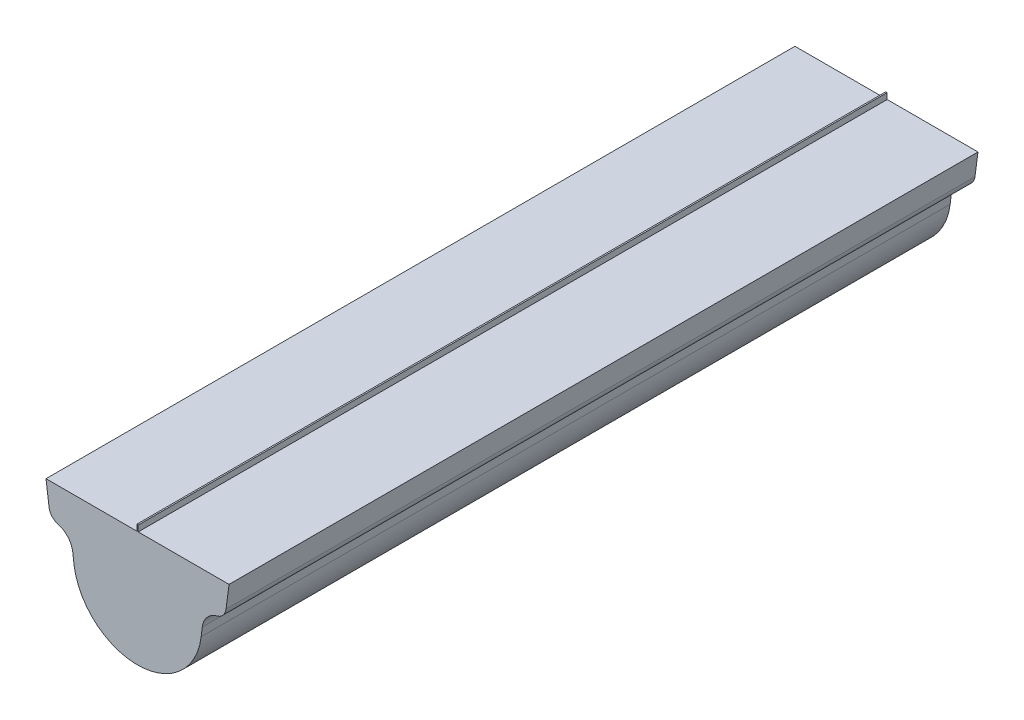
SolidWorks part; units mm, degrees
ref_plane "Front Plane" through (0, 0, 0) normal (0, 0, 1) x (1, 0, 0)
ref_plane "Top Plane" through (0, 0, 0) normal (0, 1, 0) x (1, 0, 0)
ref_plane "Right Plane" through (0, 0, 0) normal (1, 0, 0) x (0, 0, -1)
sketch "Sketch2" plane through (0, 0, 0) normal (0, 0, 1) x (1, 0, 0)
  line L0 (-2.5934, 0.0458) -> (-2.5383, -0.4019)
  line L1 (2.551, -0.3125) -> (2.5948, 0.0454)
  line L2 (3.4932, 0.7413) -> (3.6667, 2.0599)
  line L3 (-3.4918, 0.7413) -> (-3.6652, 2.0599)
  line L4 (-3.6652, 2.0599) -> (-0.0275, 2.0599)
  line L5 (0.0007, 2.3) -> (0.0007, 2.0599) construction
  line L6 (0.0289, 2.0599) -> (3.6667, 2.0599)
  line L10 (0.0289, 2.2587) -> (0.0289, 2.0599)
  line L11 (-0.0238, 2.3) -> (0.0289, 2.042) construction
  line L12 (-0.0275, 2.042) -> (0.0253, 2.3) construction
  line L13 (-0.0275, 2.2587) -> (-0.0275, 2.0599)
  line L14 (0.0289, 2.2587) -> (0.0289, 2.3)
  line L15 (0.0289, 2.3) -> (-0.0275, 2.3)
  line L20 (-0.0275, 2.3) -> (-0.0275, 2.2587)
  line L21 (0.0001, 0) -> (0.0007, 2.0599) construction
  arc A0 (-2.5934, 0.0458) -> (-3.4918, 0.7413) centre (-3.3874, -0.0519) ccw
  arc A1 (3.4932, 0.7413) -> (2.5948, 0.0454) centre (3.3889, -0.0519) ccw
  arc A2 (-2.5383, -0.4019) -> (2.551, -0.3125) centre (0.0001, 0) ccw
  arc A3 (3.6667, 2.0599) -> (-3.6652, 2.0599) centre (0.0007, -25.8067) ccw construction
  point P12 (0.0007, 2.3)
  point P15 (0.0007, 2.1799)
  point P22 (0.0007, 2.3492)
  dimension "D1" = 0.0564
extrude "Extrude1" add sketch "Sketch2" along normal mid plane 30
fillet "Fillet1" radius 0.5 2 edges at (-3.4918, 0.7413, 0) (3.4932, 0.7413, 0)
